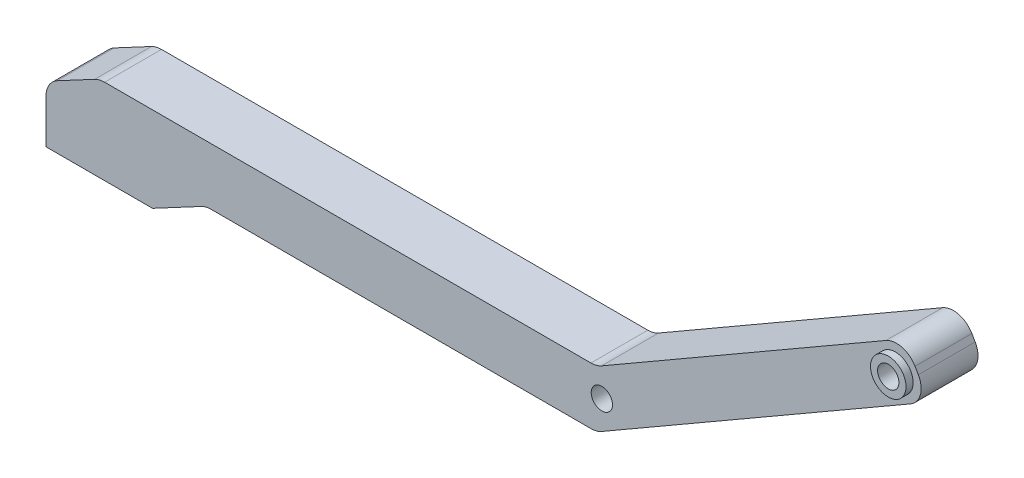
SolidWorks part; units mm, degrees
ref_plane "前视基准面" through (0, 0, 0) normal (0, 0, 1) x (1, 0, 0)
ref_plane "上视基准面" through (0, 0, 0) normal (0, 1, 0) x (1, 0, 0)
ref_plane "右视基准面" through (0, 0, 0) normal (1, 0, 0) x (0, 0, -1)
sketch "草图1" plane through (0, 0, 0) normal (0, 0, 1) x (1, 0, 0)
  line L2 (-7.5, 4) -> (-7.5, -4)
  line L3 (-7.5, -4) -> (7.5, -4)
  line L5 (-7.5, 4) -> (7.5, -4) construction
  line L6 (-7.5, -4) -> (7.5, 4) construction
  line L8 (0, 8) -> (70, 8)
  line L10 (0, 8) -> (-7.5, 4)
  line L11 (7.5, -4) -> (15, 0)
  line L12 (70, 0) -> (116.7654, 27)
  line L13 (116.7654, 27) -> (113.3013, 33)
  line L14 (70, 8) -> (113.3013, 33)
  line L15 (15, 0) -> (70, 0)
  circle A0 centre (112.0369, 28.27) radius 1.5
  circle A1 centre (70.7275, 4.42) radius 1.5
  point P0 (0, 0)
extrude "凸台-拉伸1" add sketch "草图1" along normal blind 8
fillet "圆角1" radius 3 7 edges at (15, 0, 4) (113.3013, 33, 4) (116.7654, 27, 4) (70, 0, 4) (70, 8, 4) (0, 8, 4) (-7.5, 4, 4)
sketch "草图2" plane through (0, 0, 8) normal (0, 0, 1) x (1, 0, 0)
  circle A1 centre (112.0369, 28.27) radius 2.5
  circle A3 centre (112.0369, 28.27) radius 1.5
extrude "凸台-拉伸2" add sketch "草图2" along normal blind 1
